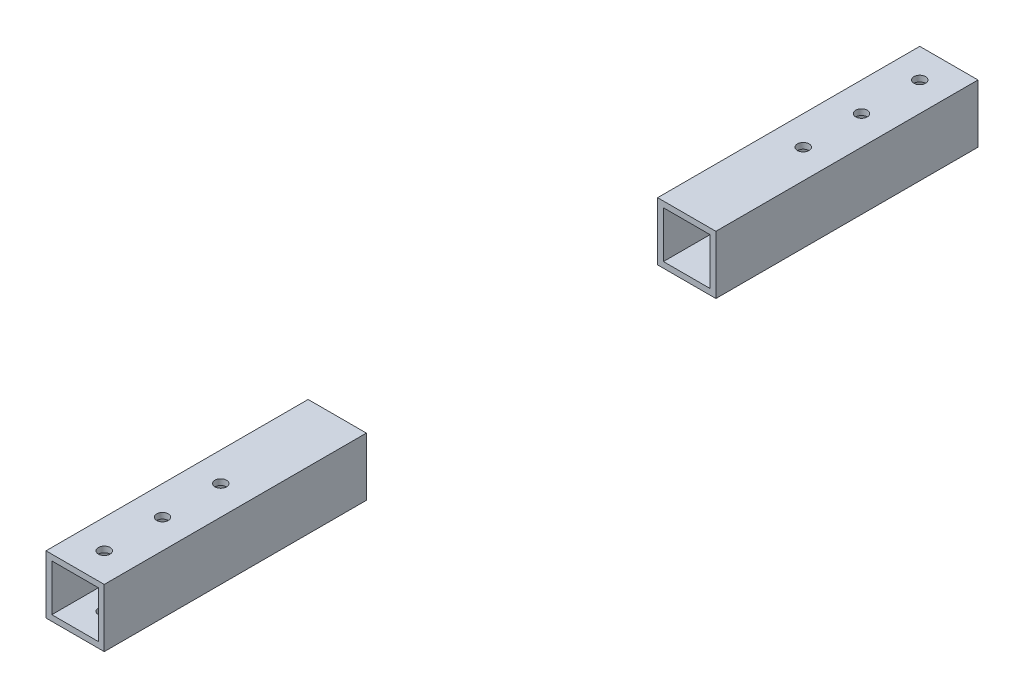
SolidWorks part; units mm, degrees
material "6061 合金"
ref_plane "前视基准面" through (0, 0, 0) normal (0, 0, 1) x (1, 0, 0)
ref_plane "上视基准面" through (0, 0, 0) normal (0, 1, 0) x (1, 0, 0)
ref_plane "右视基准面" through (0, 0, 0) normal (1, 0, 0) x (0, 0, -1)
other "Configuration Table"
sketch "草图1" plane through (0, 0, 0) normal (0, 0, 1) x (1, 0, 0)
  line L1 (0, 0) -> (20, 0)
  line L2 (0, 0) -> (0, 20)
  line L3 (0, 20) -> (20, 20)
  line L4 (20, 0) -> (20, 20)
  dimension "D1" = 20
  dimension "D2" = 20
extrude "拉伸-薄壁1" add sketch "草图1" along normal blind 300 thin thin type one direction reverse wall 2
sketch "草图2" plane through (0, 20, 0) normal (0, 1, 0) x (1, 0, 0)
  line L0 (10, -300) -> (10, -217.5608) construction
  line L1 (20, -300) -> (0, -300) construction
  line L2 (0, -150) -> (20, -150) construction
  line L3 (0, -300) -> (0, 0) construction
  line L4 (20, -300) -> (20, 0) construction
  circle A0 centre (10, -290) radius 2
  circle A1 centre (10, -270) radius 2
  circle A2 centre (10, -250) radius 2
  circle A3 centre (10, -10) radius 2
  circle A4 centre (10, -30) radius 2
  circle A5 centre (10, -50) radius 2
  dimension "D1" = 4
  dimension "D2" = 10
  dimension "D3" = 20
  dimension "D4" = 20
extrude "切除-拉伸1" cut sketch "草图2" against normal through all
sketch "草图3" plane through (0, 20, 0) normal (0, 1, 0) x (1, 0, 0)
  line L0 (0, -150) -> (20, -150) construction
  line L1 (0, -300) -> (0, 0) construction
  line L2 (20, -300) -> (20, 0) construction
  line L4 (0, -90) -> (20, -90)
  line L5 (0, -90) -> (0, -210)
  line L6 (0, -210) -> (20, -210)
  line L7 (20, -90) -> (20, -210)
  dimension "D1" = 120
extrude "切除-拉伸2" cut sketch "草图3" against normal through all
